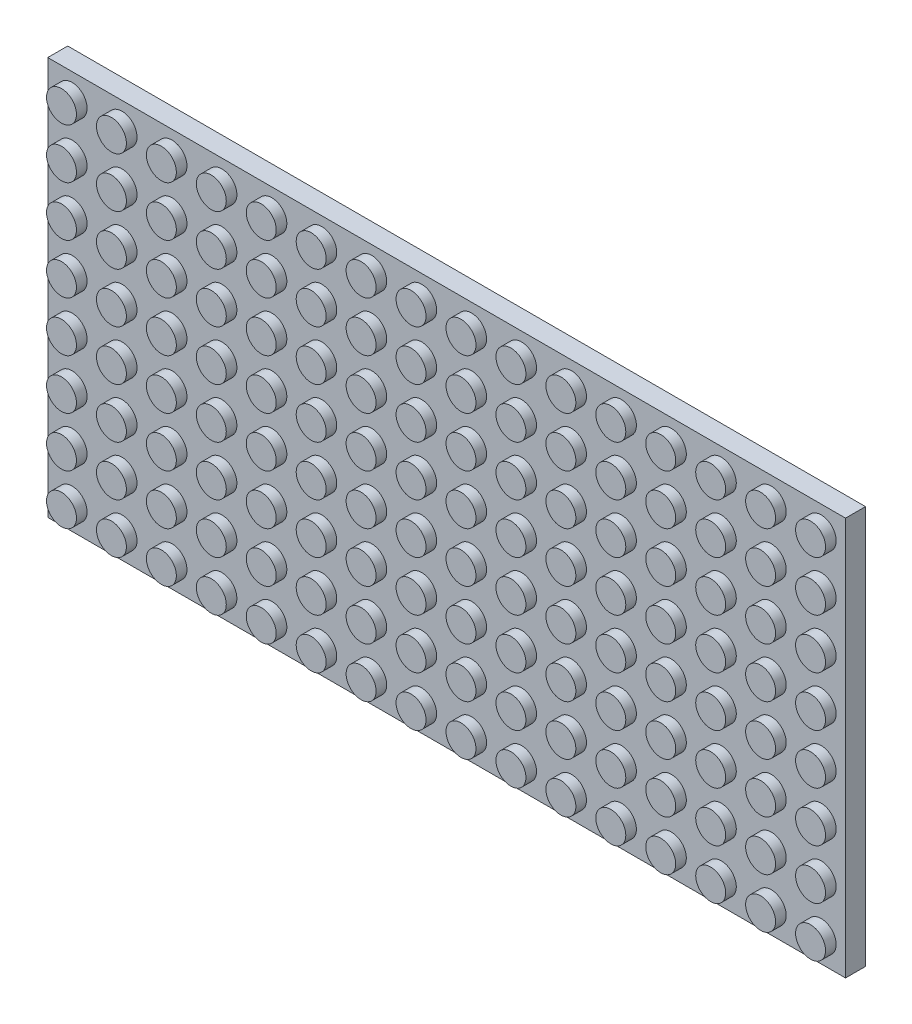
SolidWorks part; units mm, degrees
ref_plane "Спереди" through (0, 0, 0) normal (0, 0, 1) x (1, 0, 0)
ref_plane "Сверху" through (0, 0, 0) normal (0, 1, 0) x (1, 0, 0)
ref_plane "Справа" through (0, 0, 0) normal (1, 0, 0) x (0, 0, -1)
sketch "Эскиз1" plane through (0, 0, 0) normal (0, 0, 1) x (1, 0, 0)
  line L1 (-63.9, -31.9) -> (63.9, -31.9)
  line L2 (-63.9, -31.9) -> (-63.9, 31.9)
  line L3 (-63.9, 31.9) -> (63.9, 31.9)
  line L4 (63.9, -31.9) -> (63.9, 31.9)
  line L5 (-63.9, -31.9) -> (63.9, 31.9) construction
  line L6 (-63.9, 31.9) -> (63.9, -31.9) construction
  point P0 (0, 0)
  dimension "D1" = 127.8
  dimension "D2" = 63.8
extrude "Бобышка-Вытянуть1" add sketch "Эскиз1" along normal blind 3.2
sketch "Эскиз2" plane through (0, 0, 3.2) normal (0, 0, 1) x (1, 0, 0)
  line L0 (-63.9, 31.9) -> (-63.9, -31.9) construction
  line L1 (63.9, 31.9) -> (-63.9, 31.9) construction
  circle A0 centre (-60, 28) radius 2.4
  circle A1 centre (-52, 28) radius 2.4
  circle A2 centre (-44, 28) radius 2.4
  circle A3 centre (-36, 28) radius 2.4
  circle A4 centre (-28, 28) radius 2.4
  circle A5 centre (-20, 28) radius 2.4
  circle A6 centre (-12, 28) radius 2.4
  circle A7 centre (-4, 28) radius 2.4
  circle A8 centre (4, 28) radius 2.4
  circle A9 centre (12, 28) radius 2.4
  circle A10 centre (20, 28) radius 2.4
  circle A11 centre (28, 28) radius 2.4
  circle A12 centre (36, 28) radius 2.4
  circle A13 centre (44, 28) radius 2.4
  circle A14 centre (52, 28) radius 2.4
  circle A15 centre (60, 28) radius 2.4
  circle A16 centre (-52, 20) radius 2.4
  circle A17 centre (-44, 20) radius 2.4
  circle A18 centre (-36, 20) radius 2.4
  circle A19 centre (-28, 20) radius 2.4
  circle A20 centre (-20, 20) radius 2.4
  circle A21 centre (-12, 20) radius 2.4
  circle A22 centre (-4, 20) radius 2.4
  circle A23 centre (4, 20) radius 2.4
  circle A24 centre (12, 20) radius 2.4
  circle A25 centre (20, 20) radius 2.4
  circle A26 centre (28, 20) radius 2.4
  circle A27 centre (36, 20) radius 2.4
  circle A28 centre (44, 20) radius 2.4
  circle A29 centre (52, 20) radius 2.4
  circle A30 centre (60, 20) radius 2.4
  circle A31 centre (-52, 12) radius 2.4
  circle A32 centre (-44, 12) radius 2.4
  circle A33 centre (-36, 12) radius 2.4
  circle A34 centre (-28, 12) radius 2.4
  circle A35 centre (-20, 12) radius 2.4
  circle A36 centre (-12, 12) radius 2.4
  circle A37 centre (-4, 12) radius 2.4
  circle A38 centre (4, 12) radius 2.4
  circle A39 centre (12, 12) radius 2.4
  circle A40 centre (20, 12) radius 2.4
  circle A41 centre (28, 12) radius 2.4
  circle A42 centre (36, 12) radius 2.4
  circle A43 centre (44, 12) radius 2.4
  circle A44 centre (52, 12) radius 2.4
  circle A45 centre (60, 12) radius 2.4
  circle A46 centre (-52, 4) radius 2.4
  circle A47 centre (-44, 4) radius 2.4
  circle A48 centre (-36, 4) radius 2.4
  circle A49 centre (-28, 4) radius 2.4
  circle A50 centre (-20, 4) radius 2.4
  circle A51 centre (-12, 4) radius 2.4
  circle A52 centre (-4, 4) radius 2.4
  circle A53 centre (4, 4) radius 2.4
  circle A54 centre (12, 4) radius 2.4
  circle A55 centre (20, 4) radius 2.4
  circle A56 centre (28, 4) radius 2.4
  circle A57 centre (36, 4) radius 2.4
  circle A58 centre (44, 4) radius 2.4
  circle A59 centre (52, 4) radius 2.4
  circle A60 centre (60, 4) radius 2.4
  circle A61 centre (-52, -4) radius 2.4
  circle A62 centre (-44, -4) radius 2.4
  circle A63 centre (-36, -4) radius 2.4
  circle A64 centre (-28, -4) radius 2.4
  circle A65 centre (-20, -4) radius 2.4
  circle A66 centre (-12, -4) radius 2.4
  circle A67 centre (-4, -4) radius 2.4
  circle A68 centre (4, -4) radius 2.4
  circle A69 centre (12, -4) radius 2.4
  circle A70 centre (20, -4) radius 2.4
  circle A71 centre (28, -4) radius 2.4
  circle A72 centre (36, -4) radius 2.4
  circle A73 centre (44, -4) radius 2.4
  circle A74 centre (52, -4) radius 2.4
  circle A75 centre (60, -4) radius 2.4
  circle A76 centre (-52, -12) radius 2.4
  circle A77 centre (-44, -12) radius 2.4
  circle A78 centre (-36, -12) radius 2.4
  circle A79 centre (-28, -12) radius 2.4
  circle A80 centre (-20, -12) radius 2.4
  circle A81 centre (-12, -12) radius 2.4
  circle A82 centre (-4, -12) radius 2.4
  circle A83 centre (4, -12) radius 2.4
  circle A84 centre (12, -12) radius 2.4
  circle A85 centre (20, -12) radius 2.4
  circle A86 centre (28, -12) radius 2.4
  circle A87 centre (36, -12) radius 2.4
  circle A88 centre (44, -12) radius 2.4
  circle A89 centre (52, -12) radius 2.4
  circle A90 centre (60, -12) radius 2.4
  circle A91 centre (-52, -20) radius 2.4
  circle A92 centre (-44, -20) radius 2.4
  circle A93 centre (-36, -20) radius 2.4
  circle A94 centre (-28, -20) radius 2.4
  circle A95 centre (-20, -20) radius 2.4
  circle A96 centre (-12, -20) radius 2.4
  circle A97 centre (-4, -20) radius 2.4
  circle A98 centre (4, -20) radius 2.4
  circle A99 centre (12, -20) radius 2.4
  circle A100 centre (20, -20) radius 2.4
  circle A101 centre (28, -20) radius 2.4
  circle A102 centre (36, -20) radius 2.4
  circle A103 centre (44, -20) radius 2.4
  circle A104 centre (52, -20) radius 2.4
  circle A105 centre (60, -20) radius 2.4
  circle A106 centre (-52, -28) radius 2.4
  circle A107 centre (-44, -28) radius 2.4
  circle A108 centre (-36, -28) radius 2.4
  circle A109 centre (-28, -28) radius 2.4
  circle A110 centre (-20, -28) radius 2.4
  circle A111 centre (-12, -28) radius 2.4
  circle A112 centre (-4, -28) radius 2.4
  circle A113 centre (4, -28) radius 2.4
  circle A114 centre (12, -28) radius 2.4
  circle A115 centre (20, -28) radius 2.4
  circle A116 centre (28, -28) radius 2.4
  circle A117 centre (36, -28) radius 2.4
  circle A118 centre (44, -28) radius 2.4
  circle A119 centre (52, -28) radius 2.4
  circle A120 centre (60, -28) radius 2.4
  circle A121 centre (-60, 20) radius 2.4
  circle A122 centre (-60, 12) radius 2.4
  circle A123 centre (-60, 4) radius 2.4
  circle A124 centre (-60, -4) radius 2.4
  circle A125 centre (-60, -12) radius 2.4
  circle A126 centre (-60, -20) radius 2.4
  circle A127 centre (-60, -28) radius 2.4
  dimension "D1" = 3.9
  dimension "D2" = 3.9
  dimension "D3" = 16
  dimension "D4" = 8
extrude "Бобышка-Вытянуть2" add sketch "Эскиз2" along normal blind 1.7
sketch "Эскиз3" plane through (0, 0, 0) normal (0, 0, -1) x (-1, 0, 0)
  line L0 (-63.9, -31.9) -> (-63.9, 31.9) construction
  line L1 (63.9, -31.9) -> (-63.9, -31.9) construction
  circle A0 centre (-60, -28) radius 2.5
  circle A1 centre (-52, -28) radius 2.5
  circle A2 centre (-44, -28) radius 2.5
  circle A3 centre (-36, -28) radius 2.5
  circle A4 centre (-28, -28) radius 2.5
  circle A5 centre (-20, -28) radius 2.5
  circle A6 centre (-12, -28) radius 2.5
  circle A7 centre (-4, -28) radius 2.5
  circle A8 centre (4, -28) radius 2.5
  circle A9 centre (12, -28) radius 2.5
  circle A10 centre (20, -28) radius 2.5
  circle A11 centre (28, -28) radius 2.5
  circle A12 centre (36, -28) radius 2.5
  circle A13 centre (44, -28) radius 2.5
  circle A14 centre (52, -28) radius 2.5
  circle A15 centre (60, -28) radius 2.5
  circle A16 centre (-52, -20) radius 2.5
  circle A17 centre (-44, -20) radius 2.5
  circle A18 centre (-36, -20) radius 2.5
  circle A19 centre (-28, -20) radius 2.5
  circle A20 centre (-20, -20) radius 2.5
  circle A21 centre (-12, -20) radius 2.5
  circle A22 centre (-4, -20) radius 2.5
  circle A23 centre (4, -20) radius 2.5
  circle A24 centre (12, -20) radius 2.5
  circle A25 centre (20, -20) radius 2.5
  circle A26 centre (28, -20) radius 2.5
  circle A27 centre (36, -20) radius 2.5
  circle A28 centre (44, -20) radius 2.5
  circle A29 centre (52, -20) radius 2.5
  circle A30 centre (60, -20) radius 2.5
  circle A31 centre (-52, -12) radius 2.5
  circle A32 centre (-44, -12) radius 2.5
  circle A33 centre (-36, -12) radius 2.5
  circle A34 centre (-28, -12) radius 2.5
  circle A35 centre (-20, -12) radius 2.5
  circle A36 centre (-12, -12) radius 2.5
  circle A37 centre (-4, -12) radius 2.5
  circle A38 centre (4, -12) radius 2.5
  circle A39 centre (12, -12) radius 2.5
  circle A40 centre (20, -12) radius 2.5
  circle A41 centre (28, -12) radius 2.5
  circle A42 centre (36, -12) radius 2.5
  circle A43 centre (44, -12) radius 2.5
  circle A44 centre (52, -12) radius 2.5
  circle A45 centre (60, -12) radius 2.5
  circle A46 centre (-52, -4) radius 2.5
  circle A47 centre (-44, -4) radius 2.5
  circle A48 centre (-36, -4) radius 2.5
  circle A49 centre (-28, -4) radius 2.5
  circle A50 centre (-20, -4) radius 2.5
  circle A51 centre (-12, -4) radius 2.5
  circle A52 centre (-4, -4) radius 2.5
  circle A53 centre (4, -4) radius 2.5
  circle A54 centre (12, -4) radius 2.5
  circle A55 centre (20, -4) radius 2.5
  circle A56 centre (28, -4) radius 2.5
  circle A57 centre (36, -4) radius 2.5
  circle A58 centre (44, -4) radius 2.5
  circle A59 centre (52, -4) radius 2.5
  circle A60 centre (60, -4) radius 2.5
  circle A61 centre (-52, 4) radius 2.5
  circle A62 centre (-44, 4) radius 2.5
  circle A63 centre (-36, 4) radius 2.5
  circle A64 centre (-28, 4) radius 2.5
  circle A65 centre (-20, 4) radius 2.5
  circle A66 centre (-12, 4) radius 2.5
  circle A67 centre (-4, 4) radius 2.5
  circle A68 centre (4, 4) radius 2.5
  circle A69 centre (12, 4) radius 2.5
  circle A70 centre (20, 4) radius 2.5
  circle A71 centre (28, 4) radius 2.5
  circle A72 centre (36, 4) radius 2.5
  circle A73 centre (44, 4) radius 2.5
  circle A74 centre (52, 4) radius 2.5
  circle A75 centre (60, 4) radius 2.5
  circle A76 centre (-52, 12) radius 2.5
  circle A77 centre (-44, 12) radius 2.5
  circle A78 centre (-36, 12) radius 2.5
  circle A79 centre (-28, 12) radius 2.5
  circle A80 centre (-20, 12) radius 2.5
  circle A81 centre (-12, 12) radius 2.5
  circle A82 centre (-4, 12) radius 2.5
  circle A83 centre (4, 12) radius 2.5
  circle A84 centre (12, 12) radius 2.5
  circle A85 centre (20, 12) radius 2.5
  circle A86 centre (28, 12) radius 2.5
  circle A87 centre (36, 12) radius 2.5
  circle A88 centre (44, 12) radius 2.5
  circle A89 centre (52, 12) radius 2.5
  circle A90 centre (60, 12) radius 2.5
  circle A91 centre (-52, 20) radius 2.5
  circle A92 centre (-44, 20) radius 2.5
  circle A93 centre (-36, 20) radius 2.5
  circle A94 centre (-28, 20) radius 2.5
  circle A95 centre (-20, 20) radius 2.5
  circle A96 centre (-12, 20) radius 2.5
  circle A97 centre (-4, 20) radius 2.5
  circle A98 centre (4, 20) radius 2.5
  circle A99 centre (12, 20) radius 2.5
  circle A100 centre (20, 20) radius 2.5
  circle A101 centre (28, 20) radius 2.5
  circle A102 centre (36, 20) radius 2.5
  circle A103 centre (44, 20) radius 2.5
  circle A104 centre (52, 20) radius 2.5
  circle A105 centre (60, 20) radius 2.5
  circle A106 centre (-52, 28) radius 2.5
  circle A107 centre (-44, 28) radius 2.5
  circle A108 centre (-36, 28) radius 2.5
  circle A109 centre (-28, 28) radius 2.5
  circle A110 centre (-20, 28) radius 2.5
  circle A111 centre (-12, 28) radius 2.5
  circle A112 centre (-4, 28) radius 2.5
  circle A113 centre (4, 28) radius 2.5
  circle A114 centre (12, 28) radius 2.5
  circle A115 centre (20, 28) radius 2.5
  circle A116 centre (28, 28) radius 2.5
  circle A117 centre (36, 28) radius 2.5
  circle A118 centre (44, 28) radius 2.5
  circle A119 centre (52, 28) radius 2.5
  circle A120 centre (60, 28) radius 2.5
  circle A121 centre (-60, -20) radius 2.5
  circle A122 centre (-60, -12) radius 2.5
  circle A123 centre (-60, -4) radius 2.5
  circle A124 centre (-60, 4) radius 2.5
  circle A125 centre (-60, 12) radius 2.5
  circle A126 centre (-60, 20) radius 2.5
  circle A127 centre (-60, 28) radius 2.5
  dimension "D1" = 3.9
  dimension "D2" = 3.9
  dimension "D3" = 16
  dimension "D4" = 8
extrude "Вырез-Вытянуть1" cut sketch "Эскиз3" against normal blind 1.8
